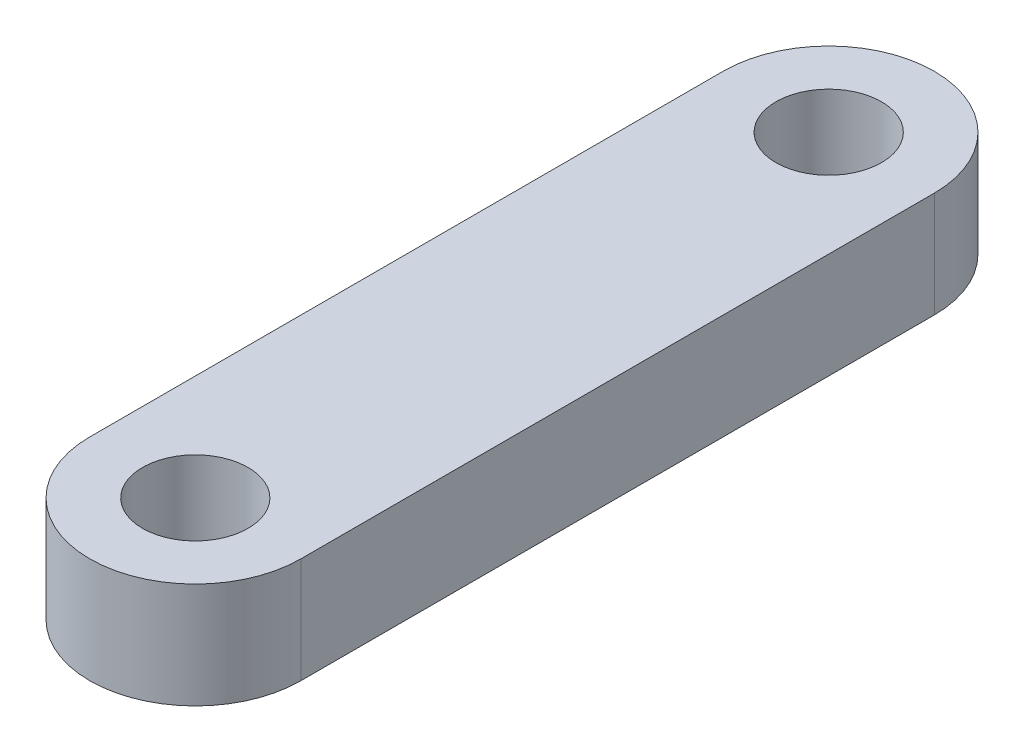
SolidWorks part; units mm, degrees
ref_plane "Front Plane" through (0, 0, 0) normal (0, 0, 1) x (1, 0, 0)
ref_plane "Top Plane" through (0, 0, 0) normal (0, 1, 0) x (1, 0, 0)
ref_plane "Right Plane" through (0, 0, 0) normal (1, 0, 0) x (0, 0, -1)
sketch "Sketch1" plane through (0, 0, 0) normal (0, 1, 0) x (1, 0, 0)
  line L0 (0, 0) -> (0, 19.05) construction
  line L1 (-3.175, 0) -> (-3.175, 19.05)
  line L2 (3.175, 0) -> (3.175, 19.05)
  arc A0 (-3.175, 0) -> (3.175, 0) centre (0, 0) ccw
  arc A1 (3.175, 19.05) -> (-3.175, 19.05) centre (0, 19.05) ccw
  circle A2 centre (0, 19.05) radius 1.5875
  circle A3 centre (0, 0) radius 1.5875
  point P3 (0, 9.525)
  dimension "D2" = 19.05
  dimension "D3" = 3.175
  dimension "D1" = 6.35
extrude "Boss-Extrude1" add sketch "Sketch1" along normal blind 3.175
equation "\"revolve_angle\"= 60"
equation "\"part_width\"= 0.125"
equation "\"notch_offset\"= 1 / 8"
equation "\"screw_diam\"= 0.125"
equation "\"D1@Sketch1\"=\"notch_offset\" * 2"
equation "\"D3@Sketch1\"=\"screw_diam\""
equation "\"D1@Boss-Extrude1\"=\"part_width\""
